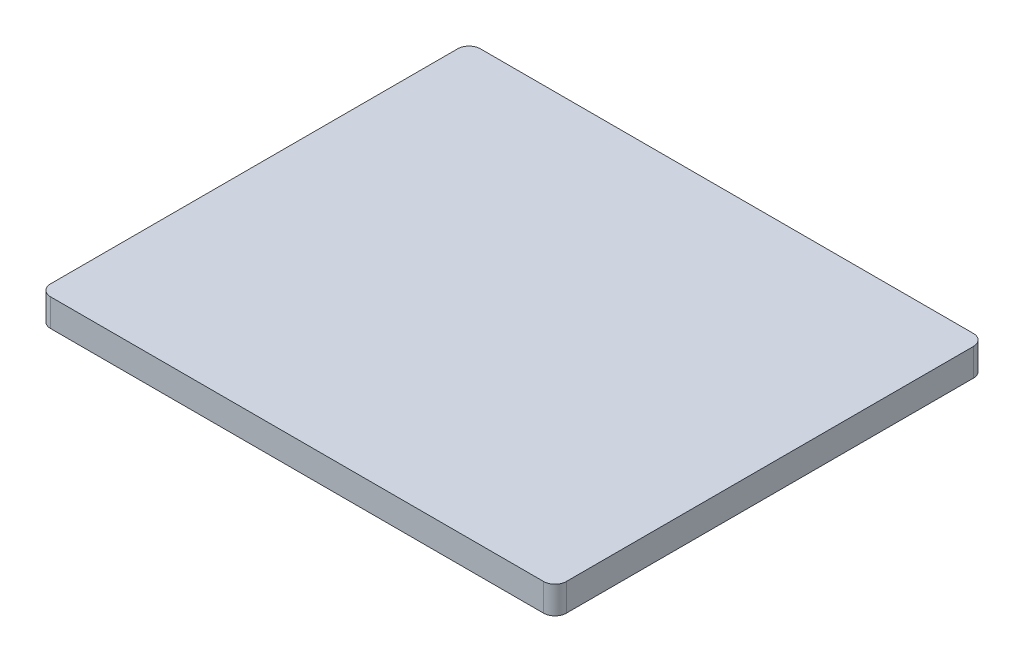
SolidWorks part; units mm, degrees
ref_plane "Alzado" through (0, 0, 0) normal (0, 0, 1) x (1, 0, 0)
ref_plane "Planta" through (0, 0, 0) normal (0, 1, 0) x (1, 0, 0)
ref_plane "Vista lateral" through (0, 0, 0) normal (1, 0, 0) x (0, 0, -1)
sketch "Croquis1" plane through (0, 0, 0) normal (0, 1, 0) x (1, 0, 0)
  line L1 (-143.396, 125) -> (143.396, 125)
  line L2 (-150, 118.396) -> (-150, -118.396)
  line L3 (-143.396, -125) -> (143.396, -125)
  line L4 (150, 118.396) -> (150, -118.396)
  line L5 (-150, 125) -> (150, -125) construction
  line L6 (-150, -125) -> (150, 125) construction
  arc A0 (143.396, 125) -> (150, 118.396) centre (143.396, 118.396) cw
  arc A1 (143.396, -125) -> (150, -118.396) centre (143.396, -118.396) ccw
  arc A2 (-150, -118.396) -> (-143.396, -125) centre (-143.396, -118.396) ccw
  arc A3 (-143.396, 125) -> (-150, 118.396) centre (-143.396, 118.396) ccw
  point P0 (0, 0)
  dimension "D3" = 6.604
  dimension "D1" = 300
  dimension "D2" = 250
extrude "Saliente-Extruir1" add sketch "Croquis1" along normal blind 16
